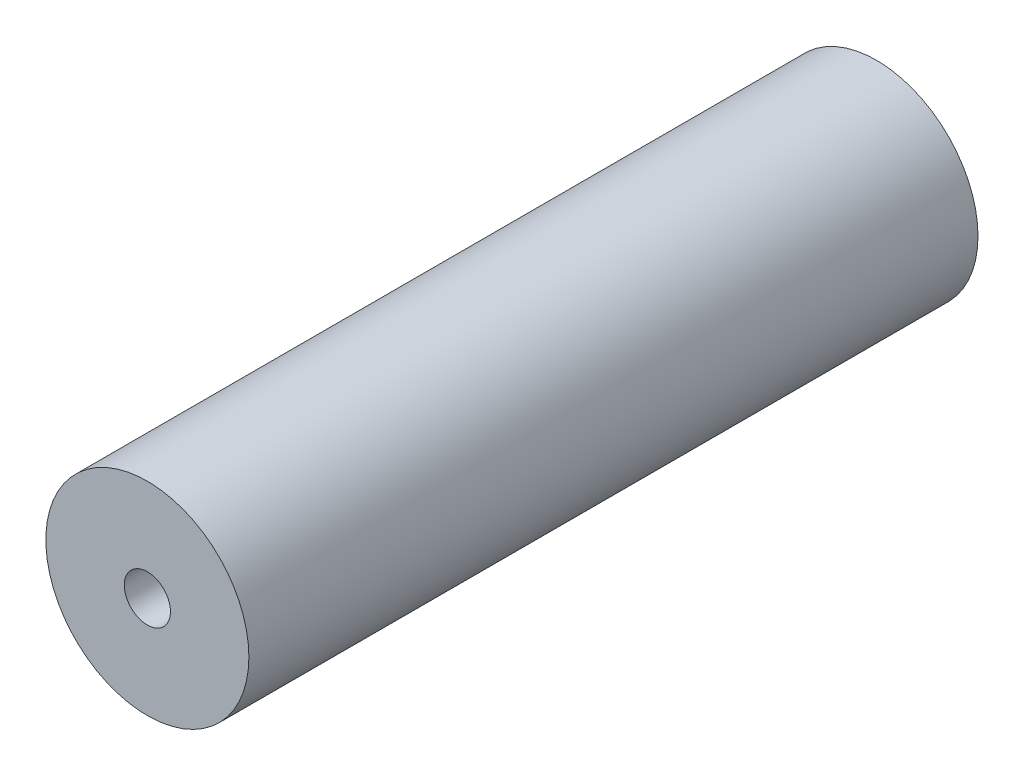
SolidWorks part; units mm, degrees
ref_plane "Front Plane" through (0, 0, 0) normal (0, 0, 1) x (1, 0, 0)
ref_plane "Top Plane" through (0, 0, 0) normal (0, 1, 0) x (1, 0, 0)
ref_plane "Right Plane" through (0, 0, 0) normal (1, 0, 0) x (0, 0, -1)
sketch "Sketch1" plane through (0, 0, 0) normal (0, 0, 1) x (1, 0, 0)
  circle A0 centre (0, 0) radius 5.5
  circle A1 centre (0, 0) radius 1.25
  dimension "D1" = 11
  dimension "D2" = 2.5
extrude "Boss-Extrude1" add sketch "Sketch1" along normal blind 39.5
